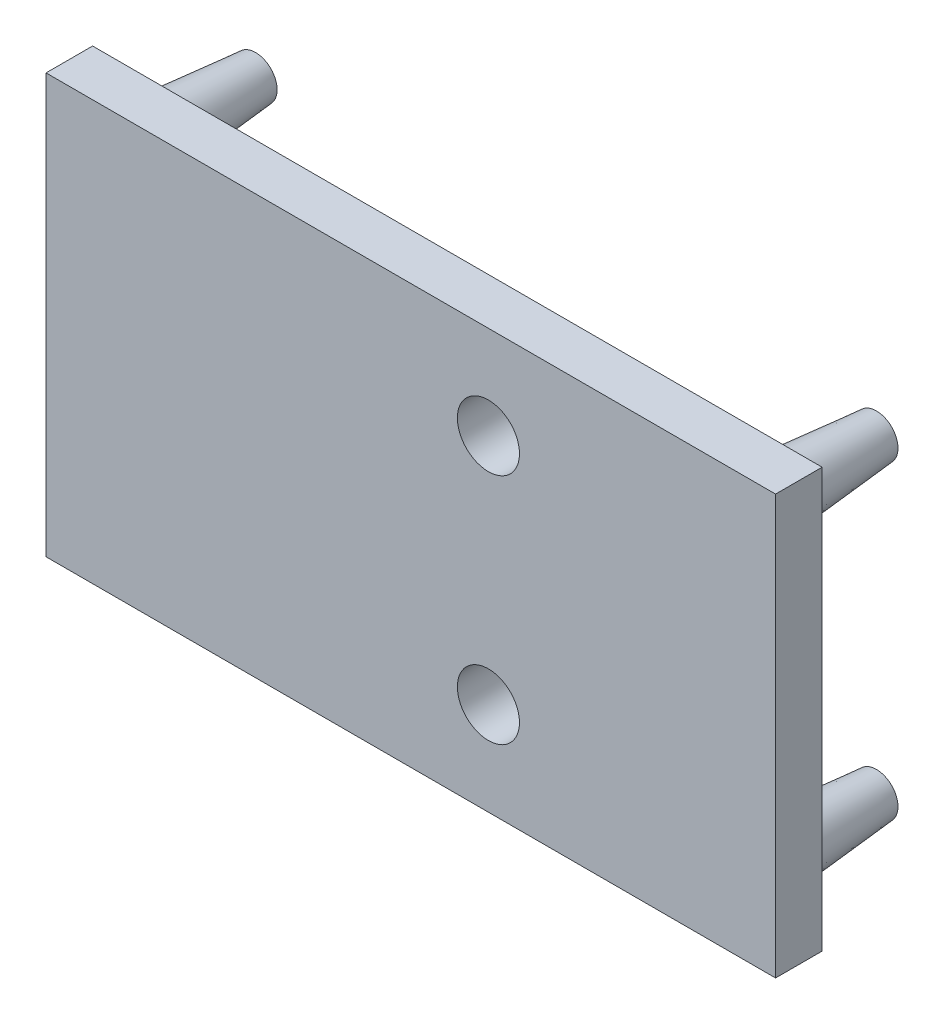
SolidWorks part; units mm, degrees
ref_plane "Front Plane" through (0, 0, 0) normal (0, 0, 1) x (1, 0, 0)
ref_plane "Top Plane" through (0, 0, 0) normal (0, 1, 0) x (1, 0, 0)
ref_plane "Right Plane" through (0, 0, 0) normal (1, 0, 0) x (0, 0, -1)
sketch "Sketch1" plane through (0, 0, 0) normal (0, 0, 1) x (1, 0, 0)
  line L1 (-23.5, -13.5) -> (23.5, -13.5)
  line L2 (-23.5, -13.5) -> (-23.5, 13.5)
  line L3 (-23.5, 13.5) -> (23.5, 13.5)
  line L4 (23.5, -13.5) -> (23.5, 13.5)
  line L5 (-23.5, -13.5) -> (23.5, 13.5) construction
  line L6 (-23.5, 13.5) -> (23.5, -13.5) construction
  line L7 (-20, 20) -> (20, 20) construction
  line L8 (-20, 20) -> (-20, -20) construction
  line L9 (-20, -20) -> (20, -20) construction
  line L10 (20, 20) -> (20, -20) construction
  line L11 (-20, 20) -> (20, -20) construction
  line L12 (-20, -20) -> (20, 20) construction
  point P0 (0, 0)
  point P6 (0, 0)
  dimension "D1" = 27
  dimension "D2" = 47
  dimension "D3" = 40
  dimension "D4" = 40
extrude "Boss-Extrude1" add sketch "Sketch1" along normal blind 3 contours L2 L1 L4 L3
sketch "Sketch2" plane through (0, 0, 0) normal (0, 0, -1) x (-1, 0, 0)
  line L1 (-20, -10) -> (20, -10) construction
  line L2 (-20, -10) -> (-20, 10) construction
  line L3 (-20, 10) -> (20, 10) construction
  line L4 (20, -10) -> (20, 10) construction
  line L5 (-20, -10) -> (20, 10) construction
  line L6 (-20, 10) -> (20, -10) construction
  circle A0 centre (-20, 10) radius 2
  circle A1 centre (20, 10) radius 2
  circle A2 centre (20, -10) radius 2
  circle A3 centre (-20, -10) radius 2
  point P0 (0, 0)
  dimension "D3" = 4
  dimension "D1" = 20
  dimension "D2" = 40
extrude "Boss-Extrude2" add sketch "Sketch2" along normal blind 7 draft 5 contours A0 | A3 | A2 | A1
sketch "Sketch3" plane through (0, 0, 3) normal (0, 0, 1) x (1, 0, 0)
  line L1 (-23.5, 13.5) -> (23.5, 13.5)
  line L2 (-23.5, 13.5) -> (-23.5, -13.5)
  line L3 (-23.5, -13.5) -> (23.5, -13.5)
  line L4 (23.5, 13.5) -> (23.5, -13.5)
  line L5 (-5, -7.5) -> (5, -7.5) construction
  line L6 (-5, -7.5) -> (-5, 7.5) construction
  line L7 (-5, 7.5) -> (5, 7.5) construction
  line L8 (5, -7.5) -> (5, 7.5) construction
  line L9 (-5, -7.5) -> (5, 7.5) construction
  line L10 (-5, 7.5) -> (5, -7.5) construction
  circle A0 centre (5, 7.5) radius 2
  circle A1 centre (5, -7.5) radius 2
  point P6 (0, 0)
  dimension "D3" = 4
  dimension "D4" = 4
  dimension "D1" = 15
  dimension "D2" = 10
extrude "Cut-Extrude1" cut sketch "Sketch3" against normal blind 5 contours A0 | A1
